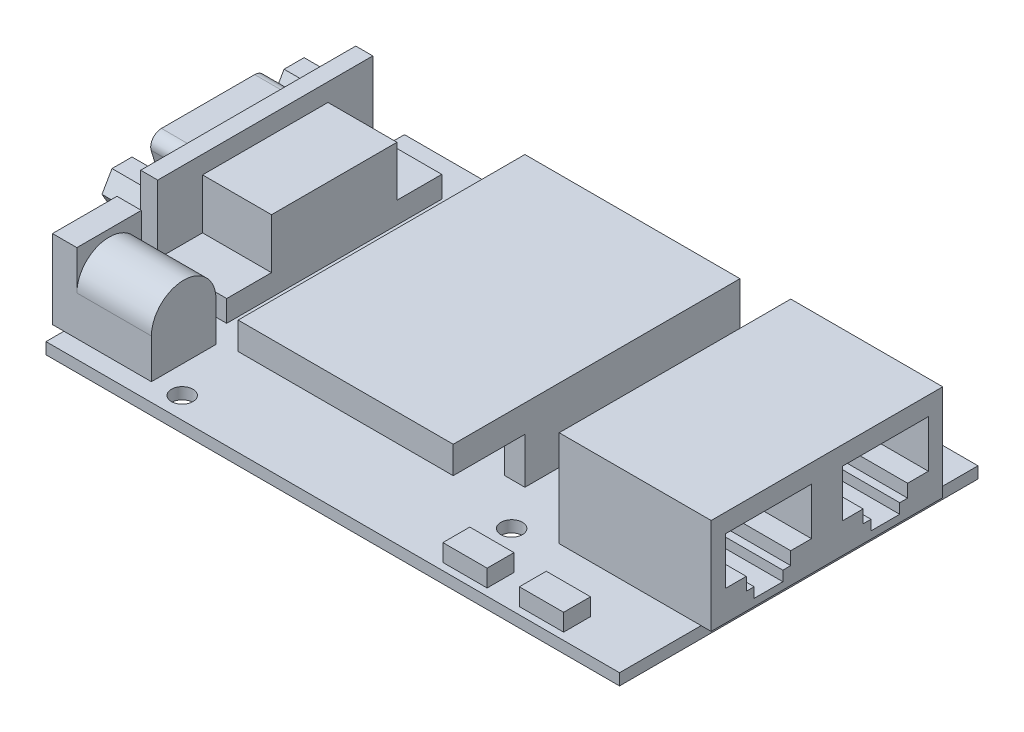
SolidWorks part; units mm, degrees
ref_plane "前视基准面" through (0, 0, 0) normal (0, 0, 1) x (1, 0, 0)
ref_plane "上视基准面" through (0, 0, 0) normal (0, 1, 0) x (1, 0, 0)
ref_plane "右视基准面" through (0, 0, 0) normal (1, 0, 0) x (0, 0, -1)
sketch "草图1" plane through (0, 0, 0) normal (0, 1, 0) x (1, 0, 0)
  line L1 (-40, -25) -> (40, -25)
  line L2 (-40, -25) -> (-40, 25)
  line L3 (-40, 25) -> (40, 25)
  line L4 (40, -25) -> (40, 25)
  line L5 (-40, -25) -> (40, 25) construction
  line L6 (-40, 25) -> (40, -25) construction
  point P0 (0, 0)
  dimension "D1" = 80
  dimension "D2" = 50
extrude "凸台-拉伸1" add sketch "草图1" along normal blind 1.6
sketch "草图2" plane through (0, 1.6, 0) normal (0, 1, 0) x (1, 0, 0)
  line L0 (40, 25) -> (-40, 25) construction
  line L1 (20.2, -13.62) -> (41.4, -13.62)
  line L2 (20.2, -13.62) -> (20.2, 18.68)
  line L3 (20.2, 18.68) -> (41.4, 18.68)
  line L4 (41.4, -13.62) -> (41.4, 18.68)
  line L5 (40, -25) -> (40, 25) construction
  dimension "D1" = 21.2
  dimension "D2" = 32.3
  dimension "D3" = 6.32
  dimension "D4" = 1.4
extrude "凸台-拉伸2" add sketch "草图2" along normal blind 13.4
sketch "草图3" plane through (41.4, 0, 0) normal (1, 0, 0) x (0, 0, -1)
  line L0 (-11.62, 12.4) -> (-11.62, 5.8)
  line L1 (-11.62, 5.8) -> (-8.72, 5.8)
  line L2 (-8.72, 5.8) -> (-8.72, 4)
  line L3 (-8.72, 4) -> (-7.62, 4)
  line L4 (-7.62, 4) -> (-7.62, 2.6)
  line L5 (-7.62, 2.6) -> (-3.62, 2.6)
  line L6 (-5.62, 2.6) -> (-5.62, 12.4) construction
  line L7 (0.38, 12.4) -> (-11.62, 12.4)
  line L8 (-3.62, 4) -> (-3.62, 2.6)
  line L9 (-2.52, 4) -> (-3.62, 4)
  line L10 (-2.52, 5.8) -> (-2.52, 4)
  line L11 (0.38, 5.8) -> (-2.52, 5.8)
  line L12 (0.38, 12.4) -> (0.38, 5.8)
  line L13 (-13.62, 15) -> (18.68, 15) construction
  line L14 (-13.62, 15) -> (-13.62, 1.6) construction
  line L15 (2.53, 15) -> (2.53, 1.6) construction
  line L16 (-13.62, 1.6) -> (18.68, 1.6) construction
  line L17 (-11.62, 12.4) -> (-11.62, 5.8)
  line L18 (-11.62, 5.8) -> (-8.72, 5.8)
  line L19 (-8.72, 5.8) -> (-8.72, 4)
  line L20 (-8.72, 4) -> (-7.62, 4)
  line L21 (-7.62, 4) -> (-7.62, 2.6)
  line L22 (-3.62, 4) -> (-3.62, 2.6)
  line L23 (-2.52, 4) -> (-3.62, 4)
  line L24 (-2.52, 5.8) -> (-2.52, 4)
  line L25 (0.38, 5.8) -> (-2.52, 5.8)
  line L26 (0.38, 12.4) -> (0.38, 5.8)
  line L27 (10.68, 2.6) -> (10.68, 12.4) construction
  line L28 (4.68, 12.4) -> (4.68, 5.8)
  line L29 (4.68, 5.8) -> (7.58, 5.8)
  line L30 (7.58, 5.8) -> (7.58, 4)
  line L31 (7.58, 4) -> (8.68, 4)
  line L32 (8.68, 4) -> (8.68, 2.6)
  line L33 (12.68, 4) -> (12.68, 2.6)
  line L34 (13.78, 4) -> (12.68, 4)
  line L35 (13.78, 5.8) -> (13.78, 4)
  line L36 (16.68, 5.8) -> (13.78, 5.8)
  line L37 (16.68, 12.4) -> (16.68, 5.8)
  line L38 (4.68, 12.4) -> (4.68, 5.8)
  line L39 (4.68, 5.8) -> (7.58, 5.8)
  line L40 (7.58, 5.8) -> (7.58, 4)
  line L41 (7.58, 4) -> (8.68, 4)
  line L42 (8.68, 4) -> (8.68, 2.6)
  line L43 (4.68, 12.4) -> (16.68, 12.4)
  line L44 (12.68, 2.6) -> (8.68, 2.6)
  line L45 (12.68, 4) -> (12.68, 2.6)
  line L46 (13.78, 4) -> (12.68, 4)
  line L47 (13.78, 5.8) -> (13.78, 4)
  line L48 (16.68, 5.8) -> (13.78, 5.8)
  line L49 (16.68, 12.4) -> (16.68, 5.8)
  point P14 (-1.07, 5.8)
  dimension "D1" = 12
  dimension "D2" = 6.2
  dimension "D3" = 4
  dimension "D4" = 6.6
  dimension "D5" = 1.8
  dimension "D6" = 9.8
  dimension "D7" = 2.6
  dimension "D8" = 2
extrude "切除-拉伸1" cut sketch "草图3" against normal blind 12.7 contours L12 L7 L0 L1 L2 L3 L4 L5 L8 L9 L10 L11 | L44 L33 L34 L35 L36 L37 L43 L28 L29 L30 L31 L32
sketch "草图4" plane through (0, 1.6, 0) normal (0, 1, 0) x (1, 0, 0)
  line L0 (-40, -25) -> (40, -25) construction
  line L1 (-19, 20.8) -> (11, 20.8)
  line L2 (-19, 20.8) -> (-19, -19.2)
  line L3 (-19, -19.2) -> (11, -19.2)
  line L4 (11, 20.8) -> (11, -19.2)
  line L5 (20.2, 18.68) -> (20.2, -13.62) construction
  dimension "D1" = 40
  dimension "D2" = 30
  dimension "D3" = 5.8
  dimension "D4" = 9.2
extrude "凸台-拉伸3" add sketch "草图4" along normal blind 10.2
sketch "草图5" plane through (0, 0, 19.2) normal (0, 0, 1) x (1, 0, 0)
  line L0 (-4, 11.8) -> (-4, -2.7591) construction
  line L1 (-19, 11.8) -> (11, 11.8) construction
  line L2 (-19, 1.6) -> (11, 1.6) construction
  line L3 (-16.13, 1.6) -> (8.13, 1.6)
  line L4 (-16.13, 1.6) -> (-16.13, 8)
  line L5 (-16.13, 8) -> (8.13, 8)
  line L6 (8.13, 1.6) -> (8.13, 8)
  line L7 (-16.13, 1.6) -> (8.13, 8) construction
  line L8 (-16.13, 8) -> (8.13, 1.6) construction
  point P4 (-4, 4.8)
  dimension "D1" = 6.4
  dimension "D2" = 24.26
extrude "切除-拉伸2" cut sketch "草图5" against normal through all
sketch "草图6" plane through (-19, 0, 0) normal (-1, 0, 0) x (0, 0, 1)
  line L1 (19.2, 1.6) -> (9.2, 1.6)
  line L2 (19.2, 1.6) -> (19.2, 8)
  line L3 (19.2, 8) -> (9.2, 8)
  line L4 (9.2, 1.6) -> (9.2, 8)
  dimension "D1" = 10
  dimension "D2" = 6.4
extrude "切除-拉伸3" cut sketch "草图6" against normal up to surface (30 mm away) up to face at (11, 6.7, -0.8)
sketch "草图7" plane through (0, 1.6, 0) normal (0, 1, 0) x (1, 0, 0)
  line L0 (14.36, -20.25) -> (20.53, -20.25)
  line L1 (25.03, -20.25) -> (31.2, -20.25)
  line L2 (25.03, -20.25) -> (25.03, -24)
  line L3 (25.03, -24) -> (31.2, -24)
  line L4 (31.2, -20.25) -> (31.2, -24)
  line L5 (14.36, -20.25) -> (14.36, -24)
  line L6 (14.36, -24) -> (20.53, -24)
  line L7 (20.53, -20.25) -> (20.53, -24)
  line L8 (40, -25) -> (40, -13.62) construction
  line L9 (-40, -25) -> (40, -25) construction
  point P4 (28.115, -24)
  point P9 (17.445, -24)
  dimension "D1" = 3.75
  dimension "D2" = 6.17
  dimension "D3" = 3.75
  dimension "D4" = 6.17
  dimension "D5" = 8.8
  dimension "D6" = 1
  dimension "D7" = 4.5
extrude "凸台-拉伸4" add sketch "草图7" along normal blind 2.4
sketch "草图8" plane through (0, 1.6, 0) normal (0, 1, 0) x (1, 0, 0)
  line L0 (40, 25) -> (-40, 25) construction
  line L1 (40, 18.68) -> (40, 25) construction
  line L2 (-40, -25) -> (40, -25) construction
  line L3 (40, -25) -> (40, -13.62) construction
  line L4 (-40, 25) -> (-40, -25) construction
  circle A0 centre (16.1, 21.7) radius 1.5
  circle A1 centre (15.05, -15.1) radius 1.5
  circle A2 centre (-24, -22) radius 1.5
  circle A3 centre (-25.7, 21.7) radius 1.5
  point P10 (0, 0)
  point P13 (0, 0)
  dimension "D1" = 3
  dimension "D5" = 3
  dimension "D6" = 3
  dimension "D7" = 3
  dimension "D2" = 3.3
  dimension "D3" = 41.8
  dimension "D4" = 23.9
  dimension "D8" = 9.9
  dimension "D9" = 24.95
  dimension "D10" = 16
  dimension "D11" = 3
extrude "切除-拉伸4" cut sketch "草图8" against normal up to surface (1.6 mm away) up to face at (0, 0, 0)
ref_plane "基准面4" through (-41.6, 0, 0) normal (-1, 0, 0) x (0, 0, 1)
sketch "草图9" plane through (-41.6, 0, 0) normal (-1, 0, 0) x (0, 0, 1)
  line L0 (-25, 1.6) -> (25, 1.6) construction
  line L1 (13.4958, 1.6) -> (22.4958, 1.6)
  line L2 (13.4958, 1.6) -> (13.4958, 7.1214)
  line L4 (22.4958, 1.6) -> (22.4958, 7.1214)
  arc A0 (22.4958, 7.1214) -> (13.4958, 7.1214) centre (17.9958, 7.1214) ccw
  dimension "D1" = 9
  dimension "D2" = 5.5214
extrude "凸台-拉伸5" add sketch "草图9" against normal blind 13.8
sketch "草图10" plane through (-41.6, 0, 0) normal (-1, 0, 0) x (0, 0, 1)
  line L0 (22.4958, 1.6) -> (22.4958, 7.1214) construction
  line L1 (13.4958, 1.6) -> (22.4958, 1.6)
  line L2 (13.4958, 1.6) -> (13.4958, 12.6)
  line L3 (13.4958, 12.6) -> (22.4958, 12.6)
  line L4 (22.4958, 1.6) -> (22.4958, 12.6)
  dimension "D1" = 11
extrude "凸台-拉伸6" add sketch "草图10" against normal blind 3.4
sketch "草图11" plane through (-41.6, 0, 0) normal (-1, 0, 0) x (0, 0, 1)
  line L0 (22.4958, 12.6) -> (13.4958, 12.6) construction
  circle A0 centre (17.9958, 7.293) radius 3.15
  circle A1 centre (17.9958, 7.293) radius 0.85
  point P4 (17.9958, 12.6)
  dimension "D1" = 6.3
  dimension "D2" = 1.7
extrude "切除-拉伸5" cut sketch "草图11" against normal blind 9.6
fillet "圆角1" radius 0.8 1 edges at (-41.6, 7.293, 18.8458)
sketch "草图12" plane through (-41.6, 0, 0) normal (-1, 0, 0) x (0, 0, 1)
  line L0 (-25, 1.6) -> (13.4958, 1.6) construction
  line L1 (-19.8042, 1.6) -> (10.1958, 1.6)
  line L2 (-19.8042, 1.6) -> (-19.8042, 14.1)
  line L3 (-19.8042, 14.1) -> (10.1958, 14.1)
  line L4 (10.1958, 1.6) -> (10.1958, 14.1)
  line L5 (13.4958, 12.6) -> (13.4958, 1.6) construction
  dimension "D1" = 30
  dimension "D2" = 12.5
  dimension "D3" = 3.3
extrude "凸台-拉伸7" add sketch "草图12" against normal blind 2.38 separate body
sketch "草图13" plane through (0, 1.6, 0) normal (0, 1, 0) x (1, 0, 0)
  line L0 (-39.22, -10.1958) -> (-39.22, 19.8042) construction
  line L1 (-39.22, 19.8042) -> (-29.6, 19.8042)
  line L2 (-39.22, 19.8042) -> (-39.22, -10.1958)
  line L3 (-39.22, -10.1958) -> (-29.6, -10.1958)
  line L4 (-29.6, 19.8042) -> (-29.6, -10.1958)
  line L5 (-39.22, -10.1958) -> (-41.6, -10.1958) construction
  line L6 (-39.22, 19.8042) -> (-41.6, 19.8042) construction
  line L7 (-41.6, -10.1958) -> (-41.6, 19.8042) construction
  dimension "D1" = 12
extrude "凸台-拉伸8" add sketch "草图13" along normal blind 3
sketch "草图14" plane through (0, 4.6, 0) normal (0, 1, 0) x (1, 0, 0)
  line L0 (-39.22, 4.8042) -> (-19.98, 4.8042) construction
  line L1 (-39.22, -10.1958) -> (-39.22, 19.8042) construction
  line L2 (-39.22, 19.8042) -> (-39.22, -10.1958) construction
  line L3 (-39.22, 13.5542) -> (-29.6, 13.5542)
  line L4 (-39.22, 13.5542) -> (-39.22, -3.9458)
  line L5 (-39.22, -3.9458) -> (-29.6, -3.9458)
  line L6 (-29.6, 13.5542) -> (-29.6, -3.9458)
  line L7 (-29.6, -10.1958) -> (-29.6, 19.8042) construction
  point P10 (-29.6, 4.8042)
  dimension "D1" = 17.5
extrude "凸台-拉伸9" add sketch "草图14" along normal blind 7
sketch "草图15" plane through (-41.6, 0, 0) normal (-1, 0, 0) x (0, 0, 1)
  line L0 (-4.8042, 14.1) -> (-4.8042, -12.7825) construction
  line L1 (10.1958, 14.1) -> (-19.8042, 14.1) construction
  line L2 (-19.8042, 14.1) -> (-19.8042, 1.6) construction
  line L3 (-14.0098, 8.28) -> (-15.407, 10.7)
  line L4 (-15.407, 10.7) -> (-18.2013, 10.7)
  line L5 (-18.2013, 10.7) -> (-19.5985, 8.28)
  line L6 (-19.5985, 8.28) -> (-18.2013, 5.86)
  line L7 (-18.2013, 5.86) -> (-15.407, 5.86)
  line L8 (-15.407, 5.86) -> (-14.0098, 8.28)
  line L9 (5.7987, 5.86) -> (4.4015, 8.28)
  line L10 (8.593, 5.86) -> (5.7987, 5.86)
  line L11 (9.9902, 8.28) -> (8.593, 5.86)
  line L12 (8.593, 10.7) -> (9.9902, 8.28)
  line L13 (5.7987, 10.7) -> (8.593, 10.7)
  line L14 (4.4015, 8.28) -> (5.7987, 10.7)
  line L15 (1.6958, 12.1) -> (-11.3042, 12.1)
  line L16 (-12.7409, 10.169) -> (-11.2409, 5.169)
  line L17 (-9.8042, 4.1) -> (0.1958, 4.1)
  line L18 (3.1326, 10.169) -> (1.6326, 5.169)
  circle A0 centre (-16.8042, 8.28) radius 2.42 construction
  circle A1 centre (-16.8042, 8.28) radius 1.5
  circle A2 centre (7.1958, 8.28) radius 2.42 construction
  circle A3 centre (7.1958, 8.28) radius 1.5
  arc A4 (1.6326, 5.169) -> (0.1958, 4.1) centre (0.1958, 5.6) cw
  arc A5 (-11.2409, 5.169) -> (-9.8042, 4.1) centre (-9.8042, 5.6) ccw
  arc A6 (3.1326, 10.169) -> (1.6958, 12.1) centre (1.6958, 10.6) ccw
  arc A7 (-11.3042, 12.1) -> (-12.7409, 10.169) centre (-11.3042, 10.6) ccw
  point P29 (-4.8042, 4.1)
  point P30 (-4.8042, 12.1)
  point P32 (1.3119, 4.1)
  point P35 (-10.9202, 4.1)
  point P38 (3.7119, 12.1)
  point P41 (-13.3202, 12.1)
  dimension "D1" = 3
  dimension "D6" = 1.5
  dimension "D2" = 4.84
  dimension "D3" = 3.4
  dimension "D4" = 3
  dimension "D5" = 8
  dimension "D7" = 10
  dimension "D8" = 13
  dimension "D9" = 2
extrude "凸台-拉伸10" add sketch "草图15" along normal blind 5.6
sketch "草图16" plane through (-47.2, 0, 0) normal (-1, 0, 0) x (0, 0, 1)
  line L0 (-4.8042, 12.1) -> (-4.8042, 4.1)
  line L1 (1.6958, 12.1) -> (-11.3042, 12.1) construction
  line L2 (-9.8042, 4.1) -> (0.1958, 4.1) construction
  circle A0 centre (-10.8042, 9.9942) radius 0.6
  circle A1 centre (-7.8042, 9.9942) radius 0.6
  circle A2 centre (-4.8042, 9.9942) radius 0.6
  circle A3 centre (-1.8042, 9.9942) radius 0.6
  circle A4 centre (1.1958, 9.9942) radius 0.6
  circle A5 centre (-9.3042, 7.224) radius 0.6
  circle A6 centre (-6.3042, 7.224) radius 0.6
  circle A7 centre (-3.3042, 7.224) radius 0.6
  circle A8 centre (-0.3042, 7.224) radius 0.6
  dimension "D1" = 1.2
  dimension "D3" = 1.2
  dimension "D5" = 1.5
  dimension "D2" = 5
  dimension "D4" = 4
extrude "切除-拉伸6" cut sketch "草图16" against normal blind 5 contours A0 | A1 | L0 A2 | L0 A2 | A3 | A4 | A8 | A7 | A6 | A5
